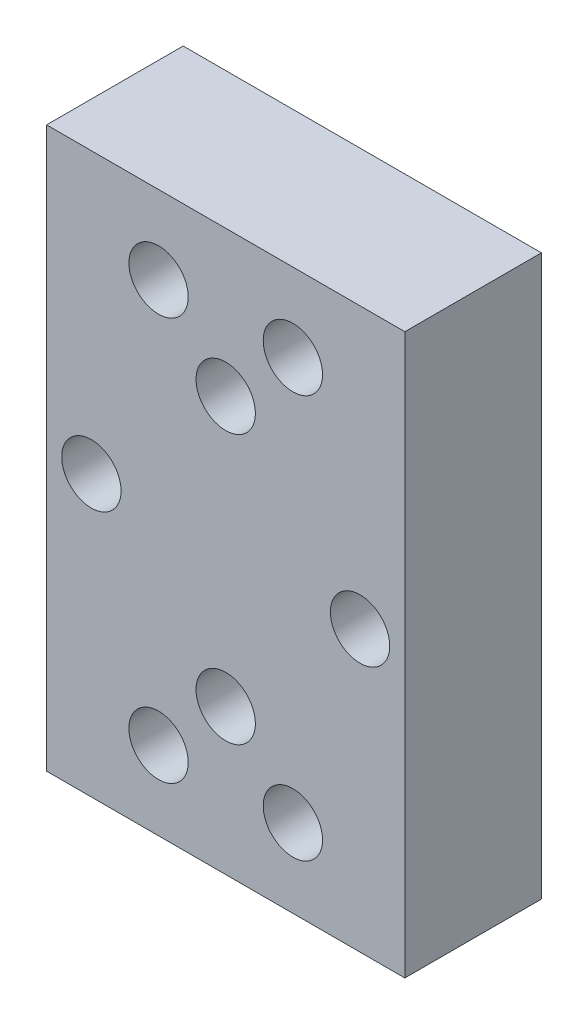
SolidWorks part; units mm, degrees
ref_plane "Front Plane" through (0, 0, 0) normal (0, 0, 1) x (1, 0, 0)
ref_plane "Top Plane" through (0, 0, 0) normal (0, 1, 0) x (1, 0, 0)
ref_plane "Right Plane" through (0, 0, 0) normal (1, 0, 0) x (0, 0, -1)
sketch "Sketch1" plane through (0, 0, 0) normal (0, 0, 1) x (1, 0, 0)
  line L0 (0, 12.5) -> (16, 12.5) construction
  line L1 (0, 0) -> (16, 0)
  line L2 (0, 0) -> (0, 25)
  line L3 (0, 25) -> (16, 25)
  line L4 (16, 0) -> (16, 25)
  line L5 (8, 25) -> (8, 0) construction
  circle A0 centre (2, 12.5) radius 1.325
  circle A1 centre (8, 18.5) radius 1.325
  circle A2 centre (5, 21.5) radius 1.325
  circle A3 centre (14, 12.5) radius 1.325
  circle A4 centre (11, 21.5) radius 1.325
  circle A5 centre (5, 3.5) radius 1.325
  circle A6 centre (11, 3.5) radius 1.325
  circle A7 centre (8, 6.5) radius 1.325
  dimension "D3" = 2.65
  dimension "D1" = 16
  dimension "D2" = 25
  dimension "D4" = 2
  dimension "D5" = 6.5
  dimension "D6" = 3.5
  dimension "D7" = 5
extrude "Boss-Extrude1" add sketch "Sketch1" along normal blind 6.1
